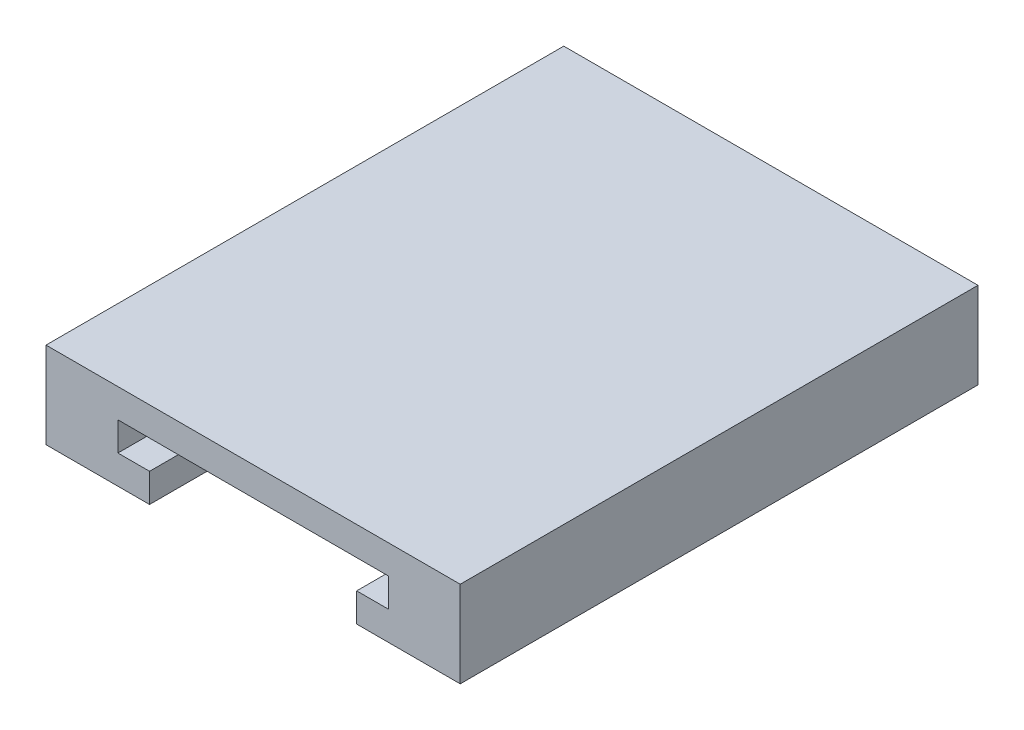
SolidWorks part; units mm, degrees
ref_plane "Front Plane" through (0, 0, 0) normal (0, 0, 1) x (1, 0, 0)
ref_plane "Top Plane" through (0, 0, 0) normal (0, 1, 0) x (1, 0, 0)
ref_plane "Right Plane" through (0, 0, 0) normal (1, 0, 0) x (0, 0, -1)
sketch "Sketch1" plane through (0, 0, 0) normal (0, 0, 1) x (1, 0, 0)
  line L1 (-3.2029, -2.2101) -> (5.7971, -2.2101)
  line L2 (-3.2029, -2.2101) -> (-3.2029, -4.7101)
  line L3 (-3.2029, -4.7101) -> (5.7971, -4.7101)
  line L4 (5.7971, -2.2101) -> (5.7971, -4.7101)
  line L5 (-3.2029, 0.2899) -> (3.0471, 0.2899)
  line L6 (-3.2029, 0.2899) -> (-3.2029, -2.2101)
  line L7 (-3.2029, -2.2101) -> (3.0471, -2.2101)
  line L8 (3.0471, 0.2899) -> (3.0471, -2.2101)
  line L13 (-3.2029, 0.2899) -> (14.7971, 0.2899)
  line L14 (-3.2029, 0.2899) -> (-3.2029, 2.7899)
  line L15 (-3.2029, 2.7899) -> (14.7971, 2.7899)
  line L16 (14.7971, 0.2899) -> (14.7971, 2.7899)
  dimension "D1" = 2.5
  dimension "D2" = 2.5
  dimension "D3" = 2.5
  dimension "D4" = 9
  dimension "D5" = 6.25
  dimension "D6" = 18
extrude "Boss-Extrude1" add sketch "Sketch1" along normal blind 45 contours L13 L16 L15 L14 L5 | L8 L5 L6 L1 | L4 L1 L2 L3
sketch "Sketch2" plane through (14.7971, 0, 0) normal (1, 0, 0) x (0, 0, -1)
  line L1 (-45, -4.7101) -> (-36.3578, -4.7101)
  line L2 (-45, -4.7101) -> (-45, -7.7101)
  line L3 (-45, -7.7101) -> (-36.3578, -7.7101)
  line L4 (-36.3578, -4.7101) -> (-36.3578, -7.7101)
  line L5 (-45, -7.7101) -> (-43, -7.7101)
  line L6 (-45, -7.7101) -> (-45, -14.7101)
  line L7 (-45, -14.7101) -> (-43, -14.7101)
  line L8 (-43, -7.7101) -> (-43, -14.7101)
  dimension "D1" = 3
  dimension "D2" = 7
  dimension "D3" = 2
mirror "Mirror1" about plane through (14.7971, 0, 45) normal (-1, 0, 0) of "Boss-Extrude1"
sketch "Sketch3" plane through (0, 0.2899, 0) normal (0, -1, 0) x (1, 0, 0)
  line L0 (14.7971, 45) -> (14.7971, 0) construction
  line L1 (14.7971, 45) -> (14.7971, 43) construction
  line L2 (14.7971, 45) -> (14.7971, 36.3578) construction
  line L3 (3.0471, 0) -> (26.5471, 0) construction
  line L4 (-3.2029, 22.5) -> (32.7971, 22.5) construction
  line L5 (-3.2029, 45) -> (-3.2029, 0) construction
  line L6 (32.7971, 45) -> (32.7971, 0) construction
  circle A0 centre (14.7971, 32.5) radius 1.25
  circle A1 centre (14.7971, 12.5) radius 1.25
  dimension "D1" = 10
extrude "Cut-Extrude1" cut sketch "Sketch3" against normal blind 45 draft 45
